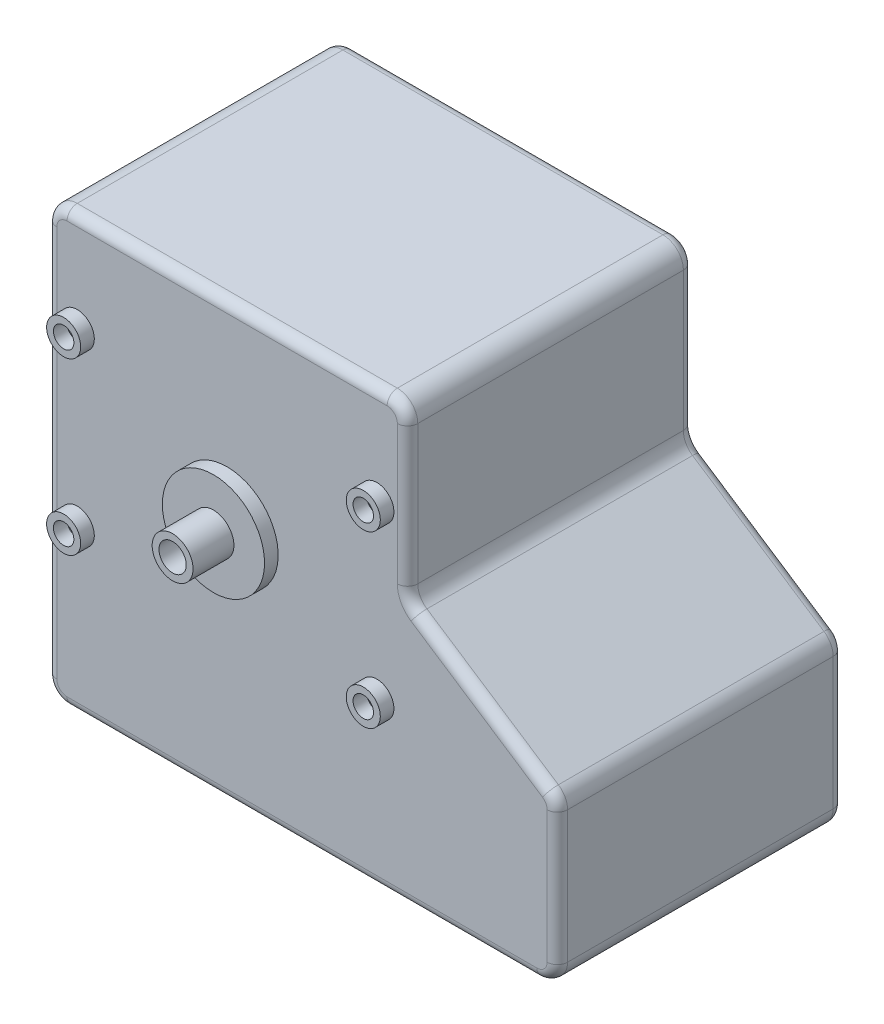
SolidWorks part; units mm, degrees
ref_plane "Front Plane" through (0, 0, 0) normal (0, 0, 1) x (1, 0, 0)
ref_plane "Top Plane" through (0, 0, 0) normal (0, 1, 0) x (1, 0, 0)
ref_plane "Right Plane" through (0, 0, 0) normal (1, 0, 0) x (0, 0, -1)
sketch "Sketch2" plane through (0, 0, 0) normal (0, 0, 1) x (1, 0, 0)
  line L0 (26.5, 6.75) -> (48.5, -7.75)
  line L1 (-26.5, -31.75) -> (26.5, -31.75)
  line L2 (-26.5, -31.75) -> (-26.5, 31.75)
  line L3 (-26.5, 31.75) -> (26.5, 31.75)
  line L4 (26.5, 6.75) -> (26.5, 31.75)
  line L5 (-26.5, -31.75) -> (26.5, 31.75) construction
  line L6 (-26.5, 31.75) -> (26.5, -31.75) construction
  line L7 (48.5, -7.75) -> (48.5, -31.75)
  line L8 (48.5, -31.75) -> (26.5, -31.75)
  line L9 (55, 0) -> (-55, 0) construction
  point P0 (0, 0)
  dimension "D1" = 63.5
  dimension "D2" = 53
  dimension "D3" = 75
  dimension "D4" = 24
  dimension "D5" = 31.75
  dimension "D6" = 25
extrude "Boss-Extrude1" add sketch "Sketch2" along normal mid plane 42
sketch "Sketch3" plane through (0, 0, 21) normal (0, 0, 1) x (1, 0, 0)
  line L0 (0, -23.1) -> (0, 23.1) construction
  line L1 (-22, -7.75) -> (22, -7.75) construction
  line L2 (-22, -7.75) -> (-22, 17.25) construction
  line L3 (-22, 17.25) -> (22, 17.25) construction
  line L4 (22, -7.75) -> (22, 17.25) construction
  line L5 (-22, -7.75) -> (22, 17.25) construction
  line L6 (-22, 17.25) -> (22, -7.75) construction
  line L7 (-26.5, -31.75) -> (48.5, -31.75) construction
  line L10 (-26.5, 31.75) -> (-26.5, -31.75) construction
  circle A0 centre (-22, 17.25) radius 1.5
  circle A1 centre (-22, -7.75) radius 1.5
  circle A2 centre (22, -7.75) radius 1.5
  circle A3 centre (22, 17.25) radius 1.5
  circle A4 centre (-22, 17.25) radius 2.5
  circle A5 centre (22, 17.25) radius 2.5
  circle A6 centre (-22, -7.75) radius 2.5
  circle A7 centre (22, -7.75) radius 2.5
  point P0 (0, 4.75)
  dimension "D4" = 3
  dimension "D5" = 5
  dimension "D1" = 36.5
  dimension "D2" = 44
  dimension "D3" = 25
  dimension "D6" = 24
  dimension "D7" = 4.5
extrude "Boss-Extrude2" add sketch "Sketch3" along normal blind 2
sketch "Sketch5" plane through (0, 0, 21) normal (0, 0, 1) x (1, 0, 0)
  line L0 (0, -23.1) -> (0, 23.1) construction
  line L1 (-26.5, -31.75) -> (48.5, -31.75) construction
  circle A0 centre (0, 3.25) radius 7.5
  dimension "D1" = 15
  dimension "D2" = 35
extrude "Boss-Extrude4" add sketch "Sketch5" along normal blind 2
fillet "Fillet1" radius 3 6 edges at (-26.5, -31.75, 0) (-26.5, 31.75, 0) (48.5, -31.75, 0) (48.5, -7.75, 0) (26.5, 6.75, 0) (26.5, 31.75, 0)
fillet "Fillet2" radius 1.5 24 edges at (26.8587, 6.9432, -21) (37.5, -0.5, -21) (48.1413, -7.9432, -21) (48.5, -19.0579, -21) (47.6213, -30.8713, -21) (11, -31.75, -21) (-25.6213, -30.8713, -21) (-26.5, 0, -21) (-25.6213, 30.8713, -21) (0, 31.75, -21) (25.6213, 30.8713, -21) (25.6213, 30.8713, 21) (26.5, 18.5579, 21) (26.8587, 6.9432, 21) (37.5, -0.5, 21) (48.1413, -7.9432, 21) (48.5, -19.0579, 21) (47.6213, -30.8713, 21) (11, -31.75, 21) (-25.6213, -30.8713, 21) (-26.5, 0, 21) (-25.6213, 30.8713, 21) (26.5, 18.5579, -21) (0, 31.75, 21)
sketch "Sketch7" plane through (0, 0, 23) normal (0, 0, 1) x (1, 0, 0)
  circle A0 centre (0, 3.25) radius 3
  dimension "D1" = 6
extrude "Boss-Extrude6" add sketch "Sketch7" along normal blind 6
sketch "Sketch8" plane through (0, 0, 29) normal (0, 0, 1) x (1, 0, 0)
  circle A0 centre (0, 3.25) radius 2
  dimension "D1" = 4
extrude "Cut-Extrude2" cut sketch "Sketch8" against normal through all
sketch "Sketch9" plane through (0, 0, -21) normal (0, 0, -1) x (-1, 0, 0)
  line L1 (-7.5, -9.25) -> (7.5, -9.25)
  line L2 (-12.5, -4.25) -> (-12.5, 10.75)
  line L3 (-7.5, 15.75) -> (7.5, 15.75)
  line L4 (12.5, -4.25) -> (12.5, 10.75)
  line L5 (-12.5, -9.25) -> (12.5, 15.75) construction
  line L6 (-12.5, 15.75) -> (12.5, -9.25) construction
  arc A0 (7.5, -9.25) -> (12.5, -4.25) centre (7.5, -4.25) ccw
  arc A1 (-7.5, -9.25) -> (-12.5, -4.25) centre (-7.5, -4.25) cw
  arc A2 (-12.5, 10.75) -> (-7.5, 15.75) centre (-7.5, 10.75) cw
  arc A3 (7.5, 15.75) -> (12.5, 10.75) centre (7.5, 10.75) cw
  point P0 (0, 3.25)
  dimension "D3" = 5
  dimension "D1" = 25
  dimension "D2" = 25
extrude "Boss-Extrude7" add sketch "Sketch9" along normal blind 8
